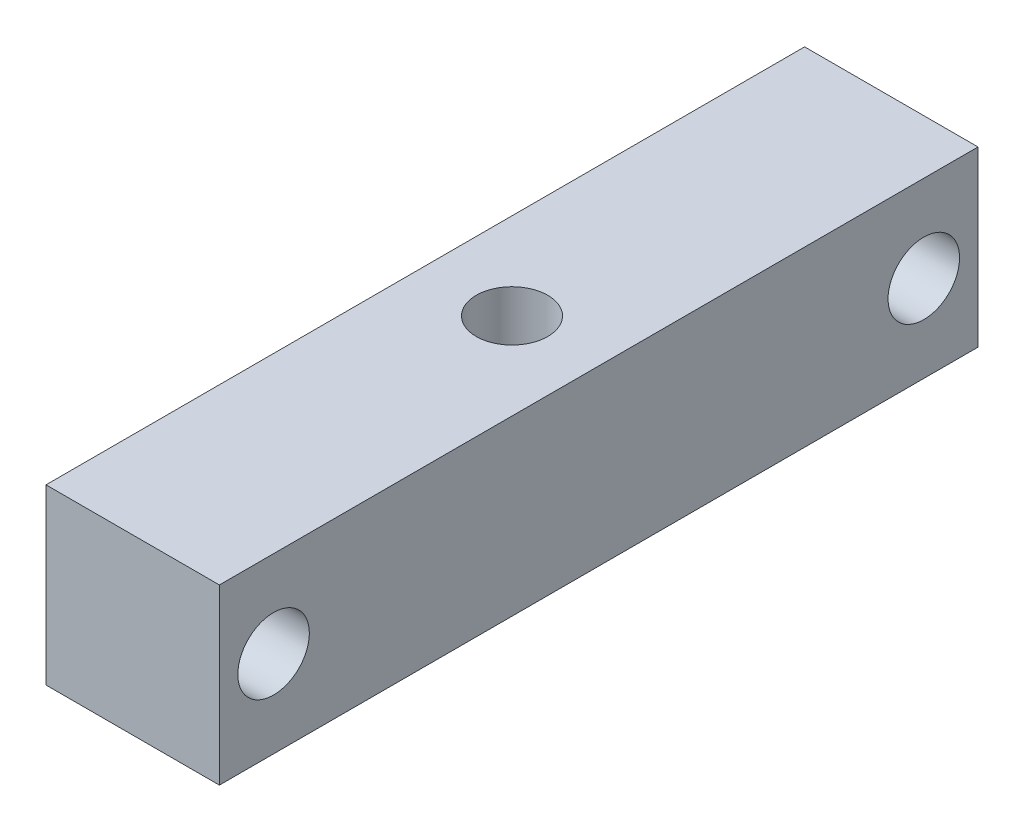
SolidWorks part; units mm, degrees
material "6061-T6 (SS)"
ref_plane "前视基准面" through (0, 0, 0) normal (0, 0, 1) x (1, 0, 0)
ref_plane "上视基准面" through (0, 0, 0) normal (0, 1, 0) x (1, 0, 0)
ref_plane "右视基准面" through (0, 0, 0) normal (1, 0, 0) x (0, 0, -1)
sketch "草图1" plane through (0, 0, 0) normal (0, 0, 1) x (1, 0, 0)
  line L1 (0, 0) -> (8, 0)
  line L2 (0, 0) -> (0, 8)
  line L3 (0, 8) -> (8, 8)
  line L4 (8, 0) -> (8, 8)
  dimension "D1" = 8
extrude "凸台-拉伸1" add sketch "草图1" along normal blind 35
sketch "草图2" plane through (8, 0, 0) normal (1, 0, 0) x (0, 0, -1)
  line L0 (-35, 4) -> (-32.5, 4) construction
  line L1 (-35, 0) -> (-35, 8) construction
  line L2 (-32.5, 4) -> (-2.5, 4) construction
  line L3 (-2.5, 4) -> (0, 4) construction
  line L4 (0, 0) -> (0, 8) construction
  circle A0 centre (-32.5, 4) radius 1.65
  circle A1 centre (-2.5, 4) radius 1.65
  dimension "D2" = 3.3
  dimension "D1" = 30
extrude "切除-拉伸1" cut sketch "草图2" against normal blind 40
cosmetic thread "装饰螺纹线1"
cosmetic thread "装饰螺纹线2"
sketch "草图3" plane through (0, 8, 0) normal (0, 1, 0) x (1, 0, 0)
  line L0 (4, -35) -> (4, 0) construction
  line L1 (8, -35) -> (0, -35) construction
  line L2 (8, 0) -> (0, 0) construction
  circle A0 centre (4, -17.5) radius 1.65
  dimension "D1" = 3.3
extrude "切除-拉伸2" cut sketch "草图3" against normal blind 40
cosmetic thread "装饰螺纹线3" parameters "D2"=3.675
sketch "草图5" plane through (8, 0, 0) normal (1, 0, 0) x (0, 0, -1)
  line L0 (-35, 8) -> (0, 8) construction
  line L1 (-30, 8) -> (-20, 8)
  line L2 (-30, 8) -> (-30, 4.5)
  line L3 (-29, 3.5) -> (-21, 3.5)
  line L4 (-20, 8) -> (-20, 4.5)
  line L5 (-20, 3.5) -> (-15, 3.5) construction
  line L6 (-15, 8) -> (-5, 8)
  line L7 (-15, 8) -> (-15, 4.5)
  line L8 (-14, 3.5) -> (-6, 3.5)
  line L9 (-5, 8) -> (-5, 4.5)
  line L10 (-17.5, 3.5) -> (-17.5, 0) construction
  line L11 (-35, 0) -> (0, 0) construction
  circle A0 centre (-32.5, 4) radius 1.65 construction
  arc A1 (-15, 4.5) -> (-14, 3.5) centre (-14, 4.5) ccw
  arc A2 (-6, 3.5) -> (-5, 4.5) centre (-6, 4.5) ccw
  arc A3 (-30, 4.5) -> (-29, 3.5) centre (-29, 4.5) ccw
  arc A4 (-21, 3.5) -> (-20, 4.5) centre (-21, 4.5) ccw
  dimension "D4" = 1
  dimension "D1" = 3.5
  dimension "D2" = 5
  dimension "D3" = 2.5
extrude "切除-拉伸3" [suppressed] cut sketch "草图5" against normal through all
